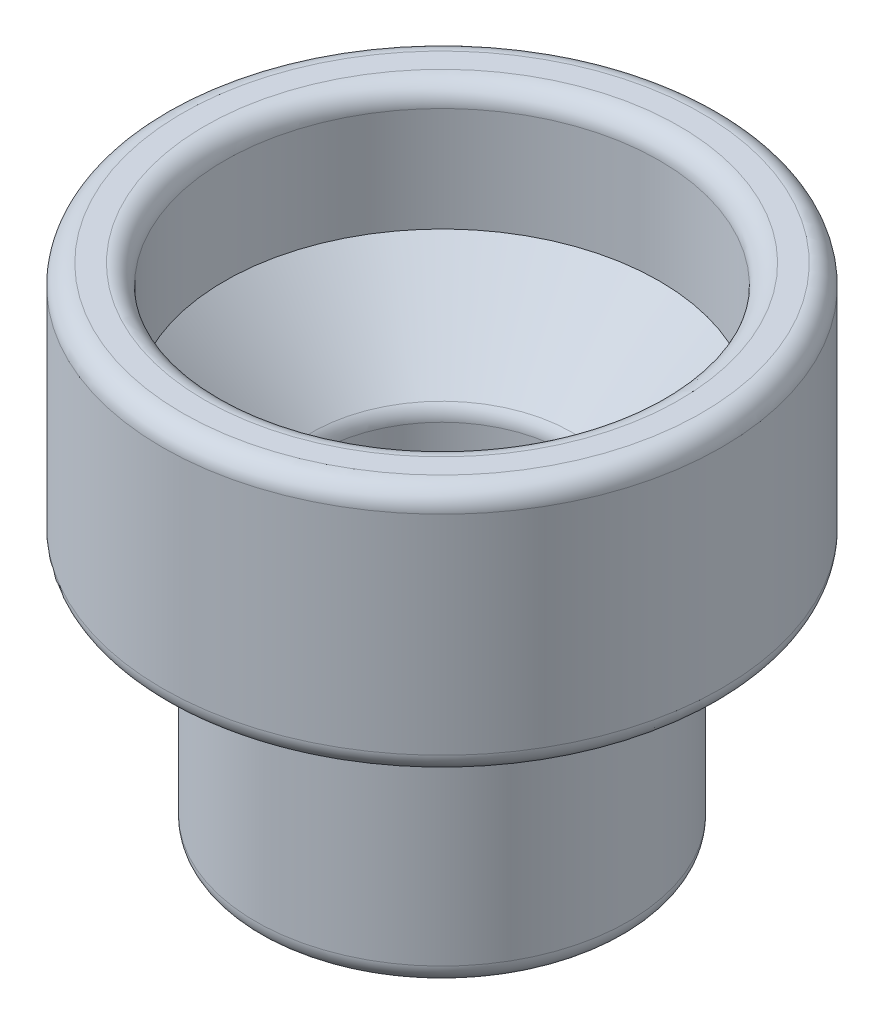
SolidWorks part; units mm, degrees
material "ABS"
ref_plane "Front Plane" through (0, 0, 0) normal (0, 0, 1) x (1, 0, 0)
ref_plane "Top Plane" through (0, 0, 0) normal (0, 1, 0) x (1, 0, 0)
ref_plane "Right Plane" through (0, 0, 0) normal (1, 0, 0) x (0, 0, -1)
sketch "Sketch1" plane through (0, 0, 0) normal (0, 0, 1) x (1, 0, 0)
  line L0 (0, 0) -> (0, 12.7) construction
  line L1 (0, 0) -> (0, -12.7) construction
  line L2 (0, -12.7) -> (6.35, -12.7) construction
  line L3 (6.35, -12.7) -> (9.525, -12.7)
  line L4 (0, 0) -> (6.35, 0) construction
  line L5 (6.35, 1.5875) -> (6.35, -12.7)
  line L6 (6.35, 0) -> (9.525, 0) construction
  line L7 (9.525, 0) -> (9.525, -12.7)
  line L8 (9.525, 0) -> (14.2875, 0)
  line L9 (14.2875, 0) -> (14.2875, 12.7)
  line L10 (9.525, 0) -> (9.4768, -0.1027) construction
  line L11 (0, 12.7) -> (11.1125, 12.7) construction
  line L12 (11.1125, 12.7) -> (14.2875, 12.7)
  line L13 (11.1125, 12.7) -> (11.1125, 6.35)
  line L14 (11.1125, 6.35) -> (6.35, 1.5875)
  dimension "D1" = 12.7
  dimension "D2" = 12.7
  dimension "D3" = 9.525
  dimension "D4" = 6.35
  dimension "D5" = 3.175
  dimension "D6" = 135
  dimension "D7" = 14.2875
  dimension "D8" = 6.35
revolve "Döndür1" add sketch "Sketch1" angle 360 about L0
fillet "Radyus1" radius 1.016 5 edges at (0, 0, -14.2875) (0, -12.7, -9.525) (0, 12.7, -14.2875) (0, 12.7, -11.1125) (0, 1.5875, -6.35)
